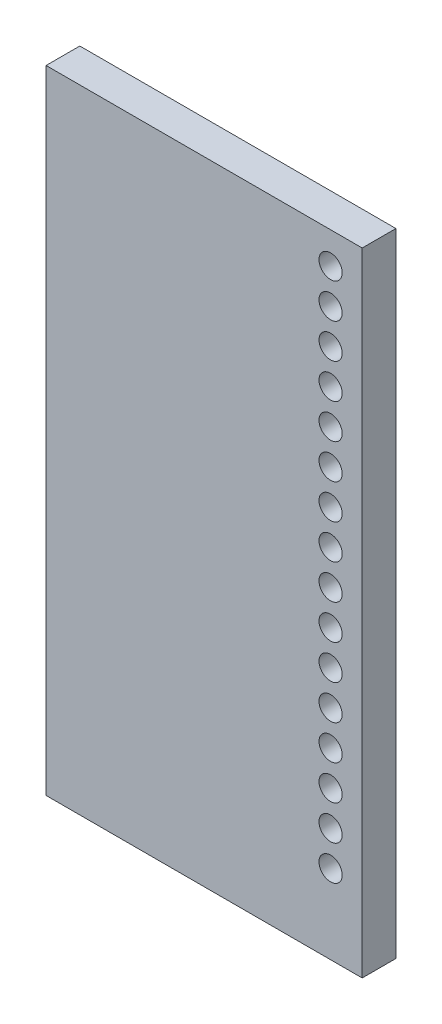
SolidWorks part; units mm, degrees
ref_plane "Front Plane" through (0, 0, 0) normal (0, 0, 1) x (1, 0, 0)
ref_plane "Top Plane" through (0, 0, 0) normal (0, 1, 0) x (1, 0, 0)
ref_plane "Right Plane" through (0, 0, 0) normal (1, 0, 0) x (0, 0, -1)
other "Bounding Box"
ref_plane "Default Plane" through (75, 0, 0) normal (-1, 0, 0) x (0, 0, 1)
sketch "Sketch1" plane through (0, 0, 0) normal (0, 0, 1) x (1, 0, 0)
  line L1 (-75, 0) -> (75, 0)
  line L2 (-75, 0) -> (-75, 300)
  line L3 (-75, 300) -> (75, 300)
  line L4 (75, 0) -> (75, 300)
  point P4 (0, 0)
  dimension "D1" = 150
  dimension "D2" = 300
extrude "Boss-Extrude1" add sketch "Sketch1" along normal blind 16
sketch "Sketch2" plane through (0, 0, 16) normal (0, 0, 1) x (1, 0, 0)
  line L0 (75, 0) -> (75, 37.5) construction
  line L1 (75, 0) -> (75, 300) construction
  line L2 (75, 37.5) -> (60, 37.5) construction
  line L3 (-75, 0) -> (75, 0) construction
  circle A0 centre (60, 37.5) radius 5.5
  dimension "D1" = 11
  dimension "D2" = 37.5
  dimension "D3" = 15
extrude "Cut-Extrude4" cut sketch "Sketch2" against normal through all
pattern_linear "LPattern1" count 16 spacing 16.5 along (0, 1, 0) of "Cut-Extrude4"
hole_wizard "#8-36 Tapped Hole1" positions "Sketch5" profile "Sketch4" tap size "#8-36" standard "ANSI Inch"
sketch "Sketch5" plane through (0, 0, 0) normal (0, -1, 0) x (-1, 0, 0)
  line L0 (-60, -8) -> (60, -8) construction
  line L2 (0, -8) -> (0, 14.7833) construction
  line L4 (-75, -16) -> (-75, 0) construction
  line L5 (75, -16) -> (75, 0) construction
  line L6 (75, -16) -> (-75, -16) construction
  line L7 (75, 0) -> (-75, 0) construction
  point P0 (-60, -8)
  point P2 (0, -8)
  point P4 (60, -8)
  dimension "D1" = 120
sketch "Sketch4" plane through (60, 0, 8) normal (1, 0, 0) x (0, 0, -1)
  line L0 (0, 0) -> (0, 26.0378)
  line L1 (0, 26.0378) -> (1.7272, 25)
  line L2 (1.7272, 25) -> (1.7272, 0)
  line L5 (1.7272, 0) -> (0, 0)
  line L10 (0, 26.0378) -> (-1.7272, 25) construction
  line L11 (0, -6.35) -> (0, 107.95) construction
  dimension "Tap Drill Dia." = 3.4544
  dimension "Tap Drill Depth" = 25
  dimension "Drill Angle" = 118
cosmetic thread "Hole Thread1" parameters "D1"=20, "D2"=4.1656
cosmetic thread "Hole Thread2" parameters "D1"=20, "D2"=4.1656
cosmetic thread "Hole Thread3" parameters "D1"=20, "D2"=4.1656
